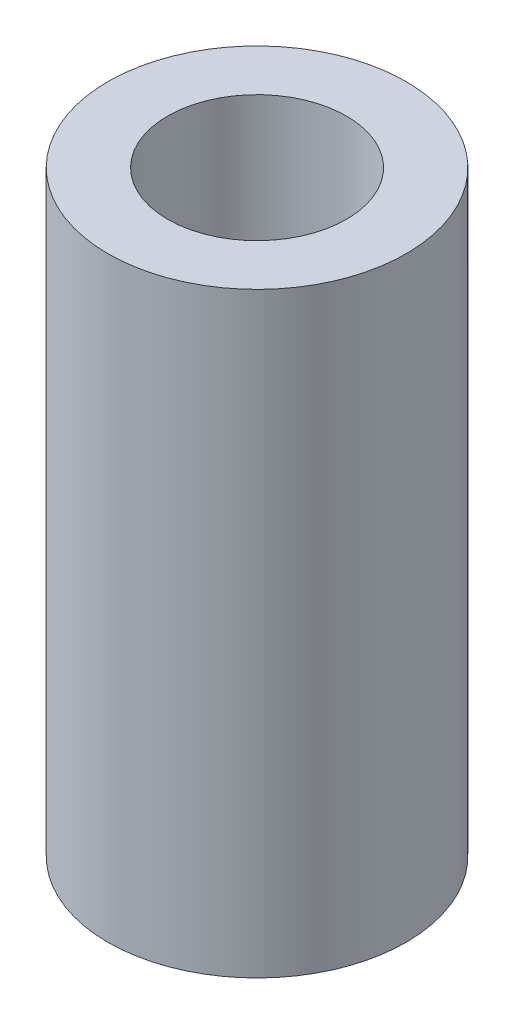
SolidWorks part; units mm, degrees
ref_plane "Front Plane" through (0, 0, 0) normal (0, 0, 1) x (1, 0, 0)
ref_plane "Top Plane" through (0, 0, 0) normal (0, 1, 0) x (1, 0, 0)
ref_plane "Right Plane" through (0, 0, 0) normal (1, 0, 0) x (0, 0, -1)
sketch "Sketch1" plane through (0, 0, 0) normal (0, 1, 0) x (1, 0, 0)
  circle A0 centre (0, 0) radius 5
  circle A1 centre (0, 0) radius 3
  dimension "D1" = 10
  dimension "D2" = 6
extrude "Boss-Extrude1" add sketch "Sketch1" along normal blind 20
